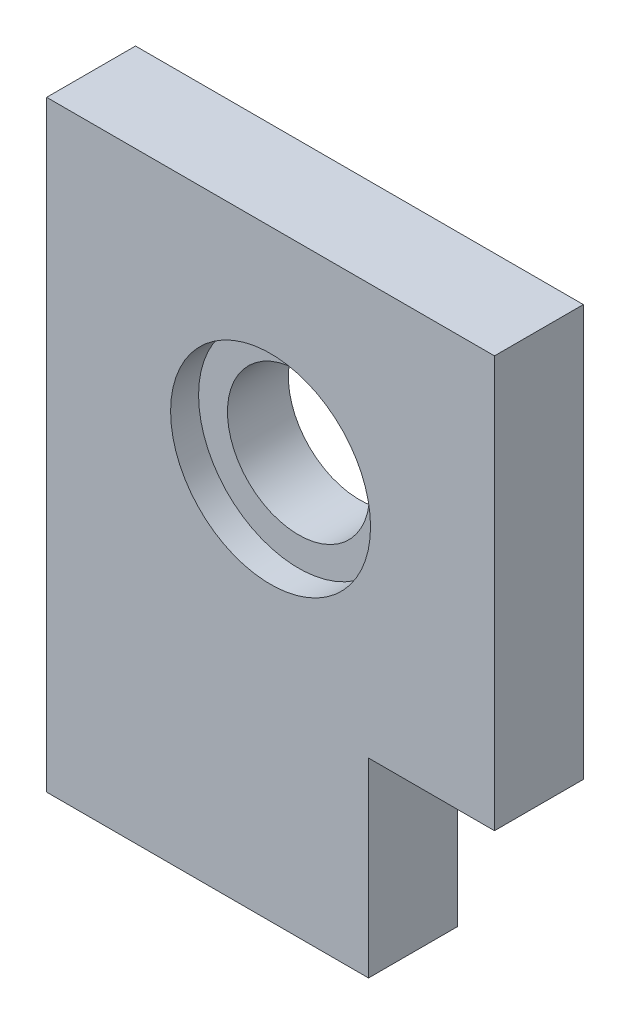
SolidWorks part; units mm, degrees
ref_plane "Front Plane" through (0, 0, 0) normal (0, 0, 1) x (1, 0, 0)
ref_plane "Top Plane" through (0, 0, 0) normal (0, 1, 0) x (1, 0, 0)
ref_plane "Right Plane" through (0, 0, 0) normal (1, 0, 0) x (0, 0, -1)
sketch "Sketch1" plane through (0, 0, 0) normal (0, 0, 1) x (1, 0, 0)
  line L1 (14, -56) -> (-32, -56)
  line L2 (-32, -56) -> (-32, 0)
  line L3 (0, 0) -> (0, -56) construction
  line L4 (-32, 0) -> (32, 0) construction
  line L5 (14, -56) -> (14, -28.775)
  line L6 (14, -28.775) -> (32, -28.775)
  line L7 (32, -28.775) -> (32, 30)
  line L8 (32, 30) -> (-32, 30)
  line L9 (-32, 30) -> (-32, 0)
  circle A0 centre (0, 0) radius 14.2875 construction
  circle A4 centre (0, 0) radius 10.16
  dimension "D1" = 32
  dimension "D2" = 46
  dimension "D6" = 20.32
  dimension "D3" = 56
  dimension "D4" = 30
  dimension "D5" = 27.225
extrude "Boss-Extrude1" add sketch "Sketch1" along normal blind 12.7
sketch "Sketch2" plane through (0, 0, 0) normal (0, 0, 1) x (1, 0, 0)
  circle A0 centre (0, 0) radius 14.2875
  dimension "D1" = 28.575
extrude "Cut-Extrude1" cut sketch "Sketch2" against normal blind 4 from surface at 12.7 starting at face at (4.6667, -18.2583, 12.7)
